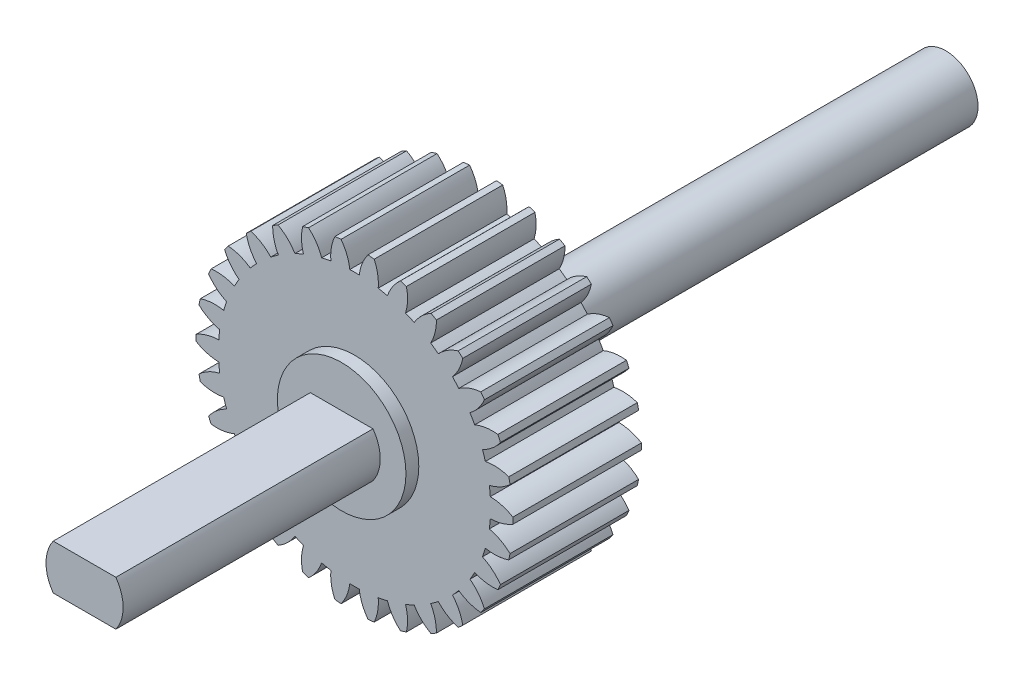
SolidWorks part; units mm, degrees
ref_plane "Front" through (0, 0, 0) normal (0, 0, 1) x (1, 0, 0)
ref_plane "Top" through (0, 0, 0) normal (0, 1, 0) x (1, 0, 0)
ref_plane "Right" through (0, 0, 0) normal (1, 0, 0) x (0, 0, -1)
sketch "Эскиз1" plane through (0, 0, 0) normal (0, 0, 1) x (1, 0, 0)
  circle A0 centre (0, 0) radius 10.5875 construction
  circle A1 centre (0, 0) radius 11.5 construction
  circle A2 centre (0, 0) radius 12.32
  circle A3 centre (0, 0) radius 10.805 construction
  dimension "D1" = 21.175
  dimension "D2" = 23
  dimension "D3" = 24.64
  dimension "D4" = 21.61
extrude "Бобышка-Вытянуть1" add sketch "Эскиз1" along normal mid plane 10
sketch "Эскиз2" plane through (0, 0, 5) normal (0, 0, 1) x (1, 0, 0)
  line L0 (-0.9448, 15.1928) -> (0, 0) construction
  line L1 (-0.7321, 11.7723) -> (-4.9391, 9.6101) construction
  line L2 (-0.6, 11.4843) -> (0.6, 11.4843) construction
  line L3 (0, 0) -> (0, 12.32) construction
  circle A0 centre (0, 0) radius 12.32 construction
  circle A1 centre (0, 0) radius 10.805 construction
  arc A2 (-1.4587, 12.7367) -> (-0.3658, 10.5812) centre (-3.8896, 10.1495) cw
  circle A3 centre (0, 0) radius 10.5875 construction
  circle A4 centre (0, 0) radius 11.5 construction
  arc A5 (1.4587, 12.7367) -> (0.3658, 10.5812) centre (3.8896, 10.1495) ccw
  arc A6 (-0.3658, 10.5812) -> (0.3658, 10.5812) centre (0, 0) cw
  circle A8 centre (0, 0) radius 12.82
  arc A9 (1.4587, 12.7367) -> (-1.4587, 12.7367) centre (0, 0) ccw
  point P3 (-0.7321, 11.7723)
  dimension "D1" = 0.525
  dimension "D2" = 1.2
  dimension "D3" = 4.7301
  dimension "D4" = 1.18
  dimension "D5" = 0.5
sketch "Эскиз4" plane through (0, 0, 0) normal (0, 1, 0) x (1, 0, 0)
  line L0 (0, 5) -> (0, -5)
  line L1 (12.32, 5) -> (-12.32, 5) construction
  line L3 (-12.32, -5) -> (12.32, -5) construction
  line L4 (0, -50) -> (0, 50) construction
  dimension "D1" = 0
curve "Кривая1"
sketch "Эскиз5" plane through (0, 0, -5) normal (0, 0, 1) x (1, 0, 0)
  line L0 (-0.9448, 15.1928) -> (0, 0) construction
  line L1 (-0.7321, 11.7723) -> (-4.9391, 9.6101) construction
  line L2 (-0.6, 11.4843) -> (0.6, 11.4843) construction
  line L3 (0, 0) -> (0, 12.32) construction
  arc A2 (-1.4587, 12.7367) -> (-0.3658, 10.5812) centre (-3.8896, 10.1495) cw
  arc A5 (1.4587, 12.7367) -> (0.3658, 10.5812) centre (3.8896, 10.1495) ccw
  arc A6 (-0.3658, 10.5812) -> (0.3658, 10.5812) centre (0, 0) cw
  arc A9 (1.4587, 12.7367) -> (-1.4587, 12.7367) centre (0, 0) ccw
  point P3 (-0.7321, 11.7723)
loft "Вырез-По сечениям1" cut profiles "Эскиз5", "Эскиз2"
pattern_circular "Круговой массив1" count 30 over 360 about axis through (0, 0, 0) along (0, 0, 1) of "Вырез-По сечениям1"
sketch "Эскиз6" plane through (0, 0, 5) normal (0, 0, 1) x (1, 0, 0)
  circle A0 centre (0, 0) radius 5
  dimension "D1" = 10
sketch "Эскиз9" plane through (0, 0, -5) normal (0, 0, -1) x (-1, 0, 0)
  circle A0 centre (0, 0) radius 2.5
  dimension "D1" = 5
extrude "Бобышка-Вытянуть6" add sketch "Эскиз6" along normal blind 1
sketch "Эскиз10" plane through (0, 0, 6) normal (0, 0, 1) x (1, 0, 0)
  line L0 (-2.4367, 1.75) -> (2.4367, 1.75)
  line L1 (-2.4367, -1.75) -> (2.4367, -1.75)
  circle A0 centre (0, 0) radius 3
  dimension "D1" = 6
  dimension "D2" = 3.5
extrude "Бобышка-Вытянуть7" add sketch "Эскиз10" along normal blind 20 contours L0 A0 L1
extrude "Бобышка-Вытянуть8" add sketch "Эскиз9" along normal blind 36
